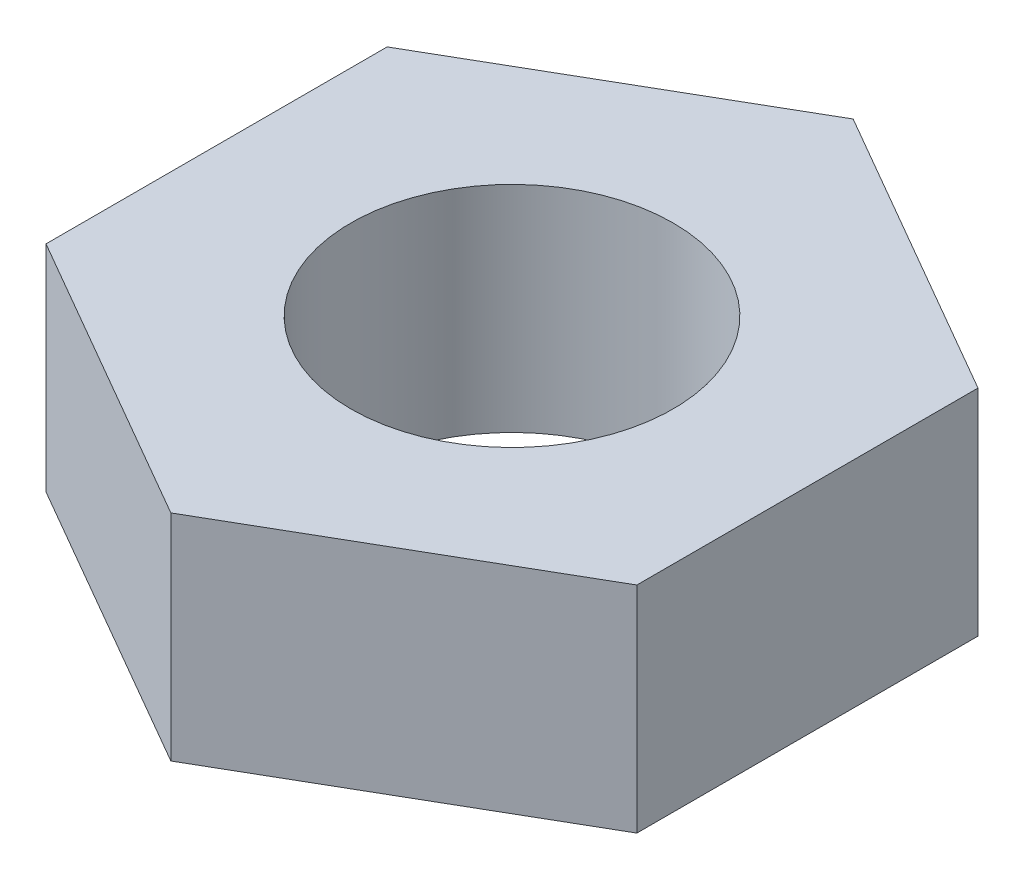
SolidWorks part; units mm, degrees
ref_plane "前视基准面" through (0, 0, 0) normal (0, 0, 1) x (1, 0, 0)
ref_plane "上视基准面" through (0, 0, 0) normal (0, 1, 0) x (1, 0, 0)
ref_plane "右视基准面" through (0, 0, 0) normal (1, 0, 0) x (0, 0, -1)
sketch "草图1" plane through (0, 0, 0) normal (0, 1, 0) x (1, 0, 0)
  line L1 (0, 3.1754) -> (-2.75, 1.5877)
  line L2 (-2.75, 1.5877) -> (-2.75, -1.5877)
  line L3 (-2.75, -1.5877) -> (0, -3.1754)
  line L4 (0, -3.1754) -> (2.75, -1.5877)
  line L5 (2.75, -1.5877) -> (2.75, 1.5877)
  line L6 (2.75, 1.5877) -> (0, 3.1754)
  circle A0 centre (0, 0) radius 2.75 construction
  circle A1 centre (0, 0) radius 1.5
  dimension "D1" = 3
  dimension "D2" = 5.5
extrude "凸台-拉伸1" add sketch "草图1" along normal blind 2
